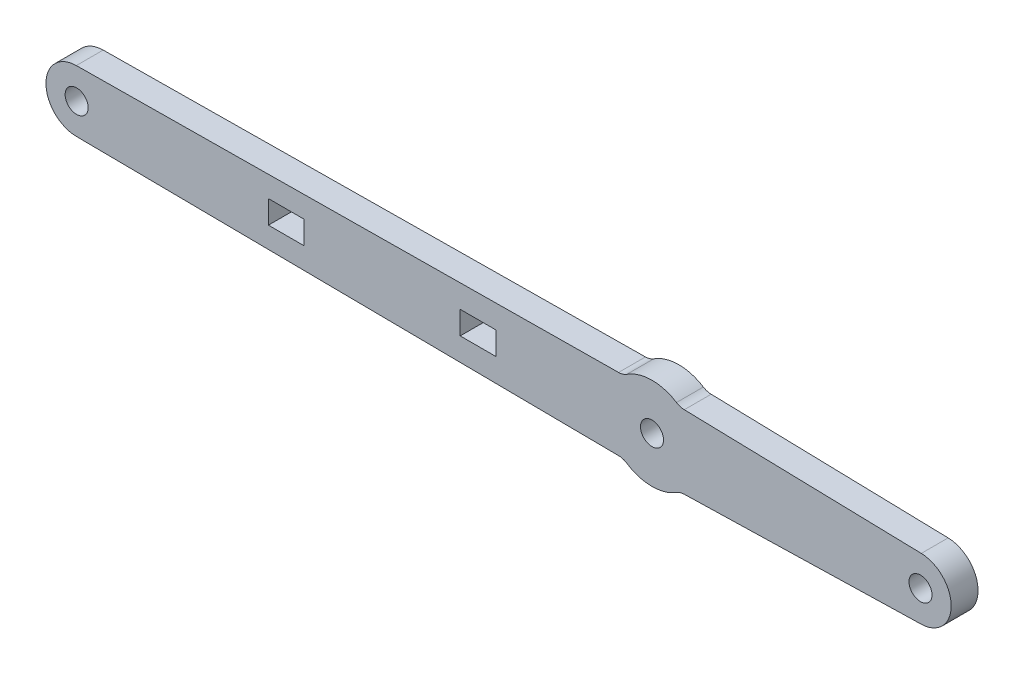
SolidWorks part; units mm, degrees
material "Balsa"
ref_plane "Front Plane" through (0, 0, 0) normal (0, 0, 1) x (1, 0, 0)
ref_plane "Top Plane" through (0, 0, 0) normal (0, 1, 0) x (1, 0, 0)
ref_plane "Right Plane" through (0, 0, 0) normal (1, 0, 0) x (0, 0, -1)
sketch "Sketch1" plane through (0, 0, 0) normal (0, 0, 1) x (1, 0, 0)
  line L0 (0, 0) -> (-75, 0) construction
  line L1 (-75.0394, 3.9998) -> (-3.7258, 4.7031)
  line L2 (-75.0394, -3.9998) -> (-3.7258, -4.7031)
  line L3 (0, 0) -> (35, 0) construction
  line L4 (-3.7258, 4.7031) -> (1.7543, 4.7031) construction
  line L5 (-3.7258, -4.7031) -> (7.547, -4.8142) construction
  line L6 (35.1002, 3.9987) -> (3.6167, 4.7874)
  line L7 (35.1002, -3.9987) -> (3.6167, -4.7874)
  line L12 (-20.3649, 1.5) -> (-25, 1.5)
  line L13 (-25, 1.5) -> (-25, -1.5)
  line L14 (-25, -1.5) -> (-20.3649, -1.5)
  line L15 (-20.3649, -1.5) -> (-20.3649, 1.5)
  line L16 (-45.3649, 1.5) -> (-50, 1.5)
  line L17 (-45.3649, -1.5) -> (-45.3649, 1.5)
  line L18 (-50, -1.5) -> (-45.3649, -1.5)
  line L19 (-50, 1.5) -> (-50, -1.5)
  circle A0 centre (-75, 0) radius 1.5
  circle A1 centre (0, 0) radius 1.5
  arc A2 (-75.0394, 3.9998) -> (-75.0394, -3.9998) centre (-75, 0) ccw
  arc A3 (-3.7258, -4.7031) -> (3.6167, -4.7874) centre (0, 0) ccw
  circle A4 centre (35, 0) radius 1.5
  arc A5 (35.1002, -3.9987) -> (35.1002, 3.9987) centre (35, 0) ccw
  arc A6 (3.6167, 4.7874) -> (-3.7258, 4.7031) centre (0, 0) ccw
  dimension "D2" = 3
  dimension "D3" = 12
  dimension "D4" = 4
  dimension "D7" = 178
  dimension "D1" = 75
  dimension "D5" = 1.13
  dimension "D6" = 35
  dimension "D9" = 25
  dimension "D10" = 3
  dimension "D11" = 4.6351
  dimension "D8" = 2
extrude "Boss-Extrude1" add sketch "Sketch1" along normal blind 3.5
fillet "Fillet1" radius 2 4 edges at (-3.7258, -4.7031, 1.75) (3.6167, -4.7874, 1.75) (-3.7258, 4.7031, 1.75) (3.6167, 4.7874, 1.75)
